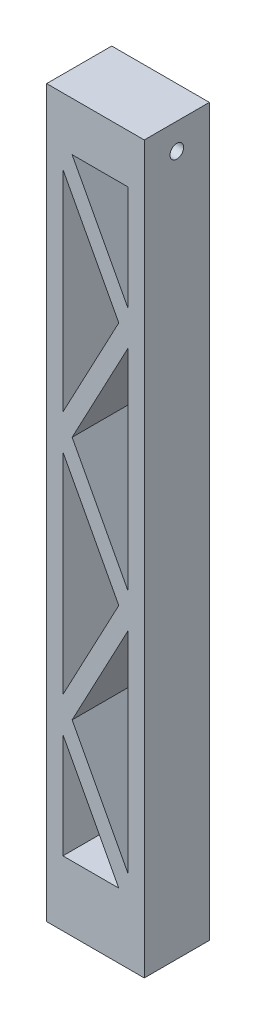
SolidWorks part; units mm, degrees
material "6061 合金"
ref_plane "前视基准面" through (0, 0, 0) normal (0, 0, 1) x (1, 0, 0)
ref_plane "上视基准面" through (0, 0, 0) normal (0, 1, 0) x (1, 0, 0)
ref_plane "右视基准面" through (0, 0, 0) normal (1, 0, 0) x (0, 0, -1)
sketch "草图1" plane through (0, 0, 0) normal (0, 1, 0) x (1, 0, 0)
  line L1 (-15, -10) -> (15, -10)
  line L2 (-15, -10) -> (-15, 10)
  line L3 (-15, 10) -> (15, 10)
  line L4 (15, -10) -> (15, 10)
  line L5 (-15, -10) -> (15, 10) construction
  line L6 (-15, 10) -> (15, -10) construction
  point P0 (0, 0)
  dimension "D1" = 20
  dimension "D2" = 30
extrude "凸台-拉伸1" add sketch "草图1" along normal blind 223
sketch "草图2" plane through (0, 0, -10) normal (0, 0, 1) x (1, 0, 0)
  line L0 (0, 0) -> (0, 248.3323) construction
  line L1 (-15, 0) -> (15, 0) construction
  line L2 (-15, 223) -> (15, 223) construction
  line L3 (-10, 208) -> (10, 170.4) construction
  line L4 (10, 170.4) -> (-10, 132.8) construction
  line L5 (-10, 132.8) -> (10, 95.2) construction
  line L6 (10, 95.2) -> (-10, 57.6) construction
  line L7 (-10, 57.6) -> (10, 20) construction
  line L8 (-10, 202.6765) -> (7.1683, 170.4)
  line L9 (15, 223) -> (15, 0) construction
  line L10 (-10, 208) -> (10, 208) construction
  line L11 (-10, 208) -> (-10, 20) construction
  line L12 (-10, 20) -> (10, 20) construction
  line L13 (10, 208) -> (10, 20) construction
  line L14 (-10, 208) -> (10, 20) construction
  line L15 (-10, 20) -> (10, 208) construction
  line L16 (7.1683, 170.4) -> (-10, 138.1235)
  line L17 (-10, 127.4765) -> (7.1683, 95.2)
  line L18 (7.1683, 95.2) -> (-10, 62.9235)
  line L19 (-10, 52.2765) -> (7.1683, 20)
  line L20 (-7.1683, 208) -> (10, 175.7235)
  line L21 (10, 165.0765) -> (-7.1683, 132.8)
  line L22 (-7.1683, 132.8) -> (10, 100.5235)
  line L23 (10, 89.8765) -> (-7.1683, 57.6)
  line L24 (-7.1683, 57.6) -> (10, 25.3235)
  line L25 (-7.7928, 209.174) -> (12.8317, 170.4) construction
  line L26 (-12.2072, 206.826) -> (7.1683, 170.4) construction
  line L27 (12.8317, 170.4) -> (-7.1683, 132.8) construction
  line L28 (7.1683, 170.4) -> (-12.8317, 132.8) construction
  line L29 (-12.8317, 132.8) -> (7.1683, 95.2) construction
  line L30 (-7.1683, 132.8) -> (12.8317, 95.2) construction
  line L31 (12.8317, 95.2) -> (-7.1683, 57.6) construction
  line L32 (7.1683, 95.2) -> (-12.8317, 57.6) construction
  line L33 (-12.8317, 57.6) -> (7.7928, 18.826) construction
  line L34 (-7.1683, 57.6) -> (12.2072, 21.174) construction
  line L35 (-7.1683, 208) -> (10, 208)
  line L36 (10, 208) -> (10, 175.7235)
  line L37 (-10, 202.6765) -> (-10, 138.1235)
  line L38 (10, 165.0765) -> (10, 100.5235)
  line L39 (-10, 127.4765) -> (-10, 62.9235)
  line L40 (10, 89.8765) -> (10, 25.3235)
  line L41 (7.1683, 20) -> (-10, 20)
  line L42 (-10, 20) -> (-10, 52.2765)
  point P2 (0, 114)
  dimension "D4" = 2.5
  dimension "D1" = 5
  dimension "D2" = 20
  dimension "D3" = 15
  dimension "D5" = 2.5
extrude "切除-拉伸1" cut sketch "草图2" along normal through all contours L41 L42 L19 | L23 L40 L24 | L39 L17 L18 | L21 L38 L22 | L37 L8 L16 | L35 L36 L20
mirror "镜向1" [suppressed] about plane through (0, 0, 0) normal (0, 0, 1)
hole_wizard "M5 螺纹孔1" positions "草图4" profile "草图3" tap size "M5" standard "GB"
sketch "草图4" plane through (0, 0, 0) normal (0, -1, 0) x (-1, 0, 0)
  line L0 (0, 0) -> (0, 7.831) construction
  line L2 (-15, -10) -> (-15, 10) construction
  point P0 (8, 0)
  point P2 (-8, 0)
  dimension "D1" = 7
sketch "草图3" plane through (-8, 0, 0) normal (1, 0, 0) x (0, 0, -1)
  line L0 (0, 0) -> (0, 15.2618)
  line L1 (0, 15.2618) -> (2.1, 14)
  line L2 (2.1, 14) -> (2.1, 0)
  line L5 (2.1, 0) -> (0, 0)
  line L10 (0, 15.2618) -> (-2.1, 14) construction
  line L11 (0, -6.35) -> (0, 107.95) construction
  dimension "螺纹孔钻头直径" = 4.2
  dimension "螺纹孔钻头深度" = 14
  dimension "导头角度" = 118
cosmetic thread "孔螺蚊线1" parameters "D1"=10, "D2"=5
cosmetic thread "孔螺蚊线2" parameters "D1"=10, "D2"=5
hole_wizard "M5 螺纹孔2" positions "草图6" profile "草图5" tap size "M5" standard "GB" end condition up to next
sketch "草图6" plane through (15, 0, 0) normal (1, 0, 0) x (0, 0, -1)
  line L0 (-10, 223) -> (10, 223) construction
  point P0 (0, 215)
  dimension "D1" = 8
sketch "草图5" plane through (15, 215, 0) normal (0, 1, 0) x (0, 0, -1)
  line L0 (0, 0) -> (0, 30)
  line L1 (0, 30) -> (2.1, 30)
  line L2 (2.1, 30) -> (2.1, 0)
  line L5 (2.1, 0) -> (0, 0)
  line L11 (0, -6.35) -> (0, 107.95) construction
  dimension "通孔螺纹孔钻头直径" = 4.2
  dimension "通孔螺纹孔钻头深度" = 30
cosmetic thread "孔螺蚊线3" parameters "D2"=5
